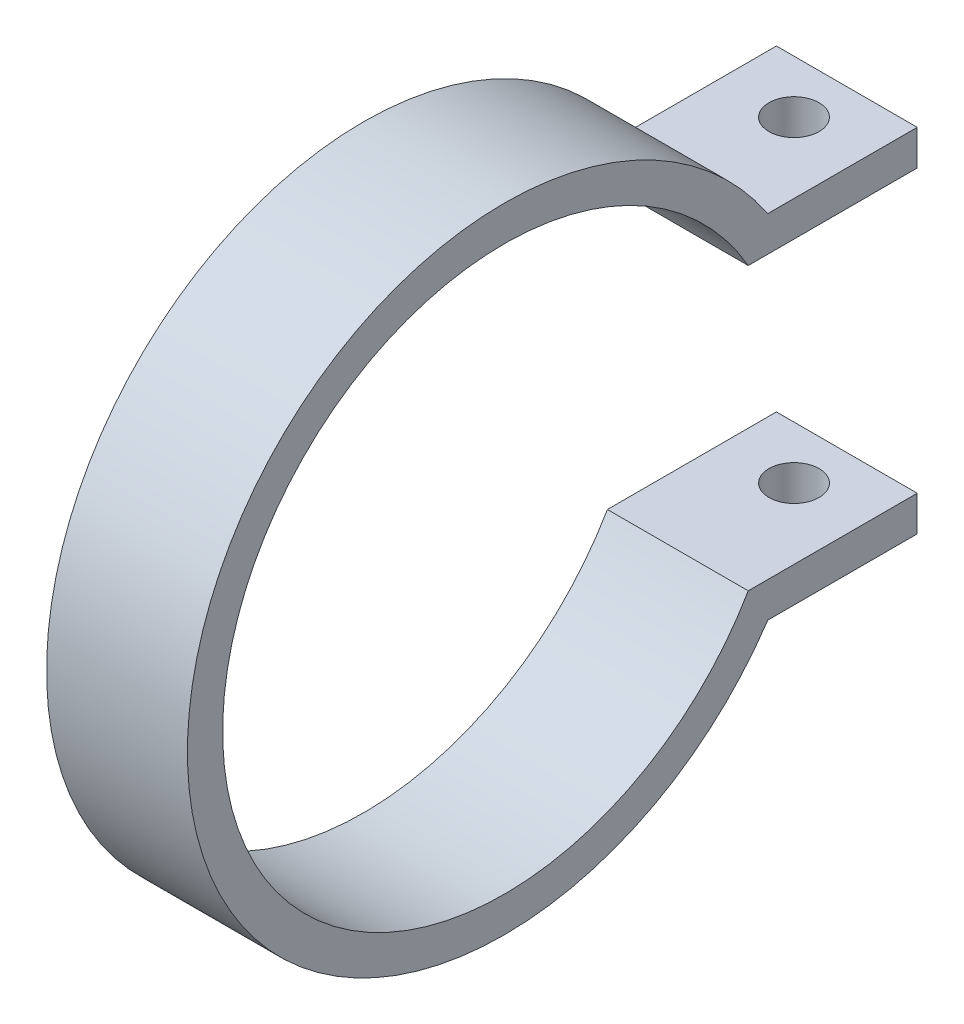
SolidWorks part; units mm, degrees
material "6061-T6 (SS)"
ref_plane "Front Plane" through (0, 0, 0) normal (1, 0, 0) x (0, 1, 0)
ref_plane "Top Plane" through (0, 0, 0) normal (0, 0, 1) x (0, 1, 0)
ref_plane "Right Plane" through (0, 0, 0) normal (0, 1, 0) x (-1, 0, 0)
sketch "Sketch2" plane through (0, 0, 0) normal (1, 0, 0) x (0, 1, 0)
  line L0 (-6.35, -10.9985) -> (6.35, -10.9985) construction
  line L1 (-6.35, -10.9985) -> (-6.35, -18.6185)
  line L2 (6.35, -10.9985) -> (6.35, -18.6185)
  line L3 (-7.9375, -11.8798) -> (-7.9375, -18.6185)
  line L4 (-7.9375, -18.6185) -> (-6.35, -18.6185)
  line L5 (6.35, -18.6185) -> (7.9375, -18.6185)
  line L6 (7.9375, -18.6185) -> (7.9375, -11.8798)
  arc A0 (6.35, -10.9985) -> (-6.35, -10.9985) centre (0, 0) ccw
  arc A1 (7.9375, -11.8798) -> (-7.9375, -11.8798) centre (0, 0) ccw
  dimension "D2" = 12.7
  dimension "D4" = 14.2875
  dimension "D1" = 12.7
  dimension "D3" = 7.62
  dimension "D5" = 1.5875
  dimension "D6" = 1.5875
extrude "Boss-Extrude1" add sketch "Sketch2" along normal blind 6.35
sketch "Sketch3" plane through (0, -7.9375, 0) normal (0, -1, 0) x (1, 0, 0)
  line L1 (3.175, -11.8798) -> (3.175, -18.6185) construction
  line L2 (6.35, -11.8798) -> (0, -11.8798) construction
  line L3 (6.35, -18.6185) -> (0, -18.6185) construction
  point P9 (3.175, -16.2373)
  dimension "D1" = 2.3813
hole_wizard "Tap Drill for #4-40 Tap1" positions "Sketch3" profile "Sketch4" hole size "#4-40" standard "ANSI Inch" end condition through all
sketch "Sketch4" plane through (3.175, -7.9375, -16.2373) normal (1, 0, 0) x (0, 0, -1)
  line L0 (0, 0) -> (0, 22.225)
  line L1 (0, 22.225) -> (1.1303, 22.225)
  line L2 (1.1303, 22.225) -> (1.1303, 0)
  line L5 (1.1303, 0) -> (0, 0)
  line L11 (0, -6.35) -> (0, 107.95) construction
  dimension "Thru Hole Dia." = 2.2606
  dimension "Thru Hole Depth" = 22.225
